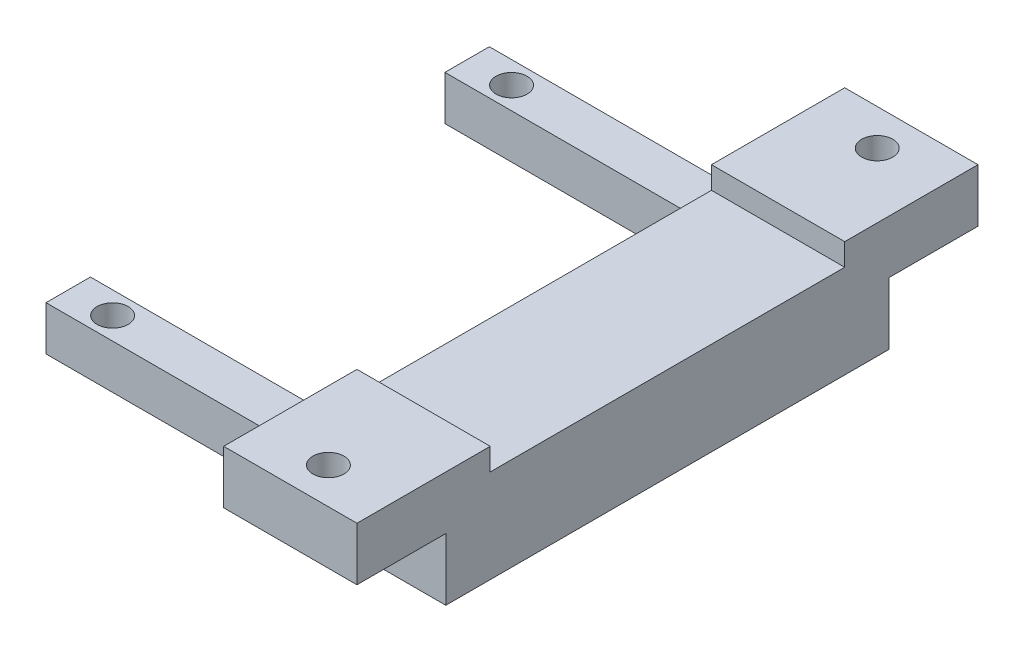
SolidWorks part; units mm, degrees
ref_plane "Front Plane" through (0, 0, 0) normal (0, 0, 1) x (1, 0, 0)
ref_plane "Top Plane" through (0, 0, 0) normal (0, 1, 0) x (1, 0, 0)
ref_plane "Right Plane" through (0, 0, 0) normal (1, 0, 0) x (0, 0, -1)
sketch "Sketch1" plane through (0, 0, 0) normal (0, 1, 0) x (1, 0, 0)
  line L1 (0, -24.95) -> (15, -24.95)
  line L2 (0, -24.95) -> (0, 24.95)
  line L3 (0, 24.95) -> (15, 24.95)
  line L4 (15, -24.95) -> (15, 24.95)
  point P4 (0, 0)
  dimension "D1" = 49.9
  dimension "D2" = 15
extrude "Boss-Extrude1" add sketch "Sketch1" along normal blind 2
sketch "Sketch2" plane through (0, 2, 0) normal (0, 1, 0) x (1, 0, 0)
  line L0 (15, -24.95) -> (15, 24.95) construction
  line L1 (15, -24.95) -> (-30, -24.95)
  line L2 (15, -24.95) -> (15, -19.95)
  line L3 (15, -19.95) -> (-30, -19.95)
  line L4 (-30, -24.95) -> (-30, -19.95)
  line L5 (15, 24.95) -> (-30, 24.95)
  line L6 (15, 24.95) -> (15, 19.95)
  line L7 (15, 19.95) -> (-30, 19.95)
  line L8 (-30, 24.95) -> (-30, 19.95)
  line L9 (0, 24.95) -> (0, -24.95) construction
  line L10 (15, 24.95) -> (0, 24.95) construction
  dimension "D1" = 30
  dimension "D2" = 5
  dimension "D3" = 5
  dimension "D4" = 0
  dimension "D5" = 30
extrude "Boss-Extrude2" add sketch "Sketch2" along normal blind 5
sketch "Sketch3" plane through (0, 7, 0) normal (0, 1, 0) x (1, 0, 0)
  line L0 (0, 19.95) -> (0, -19.95) construction
  line L2 (-30, -19.95) -> (-30, -24.95) construction
  line L3 (0, 0) -> (-23.1391, 0) construction
  circle A0 centre (-25, -22.45) radius 1.75
  circle A2 centre (-25, 22.45) radius 1.75
  point P7 (-30, -22.45)
  dimension "D2" = 3.5
  dimension "D1" = 25
extrude "Cut-Extrude1" cut sketch "Sketch3" against normal through all
sketch "Sketch4" plane through (0, 0, 0) normal (0, 1, 0) x (1, 0, 0)
  line L1 (0, -24.95) -> (15, -24.95)
  line L2 (0, -24.95) -> (0, 24.95)
  line L3 (0, 24.95) -> (15, 24.95)
  line L4 (15, -24.95) -> (15, 24.95)
  dimension "D1" = 49.9
  dimension "D2" = 15
extrude "Boss-Extrude3" add sketch "Sketch4" along normal blind 13
sketch "Sketch5" plane through (0, 0, -24.95) normal (0, 0, -1) x (-1, 0, 0)
  line L1 (-15, 13) -> (0, 13)
  line L2 (-15, 13) -> (-15, 7)
  line L3 (-15, 7) -> (0, 7)
  line L4 (0, 13) -> (0, 7)
  point P6 (0, 0)
extrude "Boss-Extrude4" add sketch "Sketch5" along normal blind 10
sketch "Sketch6" plane through (0, 13, 0) normal (0, 1, 0) x (1, 0, 0)
  circle A0 centre (7.7226, 30.8857) radius 1.75
  point P2 (0, 0)
  point P5 (7.7226, 30.8857)
  dimension "D1" = 3.5
extrude "Cut-Extrude2" cut sketch "Sketch6" against normal through all
mirror "Mirror1" about plane through (0, 0, 0) normal (0, 0, 1) of "Cut-Extrude2", "Boss-Extrude4"
sketch "Sketch7" plane through (0, 13, 0) normal (0, 1, 0) x (1, 0, 0)
  line L0 (15, -34.95) -> (15, 34.95) construction
  line L1 (0, 19.95) -> (15, 19.95)
  line L2 (0, 19.95) -> (0, -19.95)
  line L3 (0, -19.95) -> (15, -19.95)
  line L4 (15, 19.95) -> (15, -19.95)
  line L5 (0, -19.95) -> (-30, -19.95) construction
  dimension "D1" = 0
extrude "Cut-Extrude3" cut sketch "Sketch7" against normal blind 2.5
